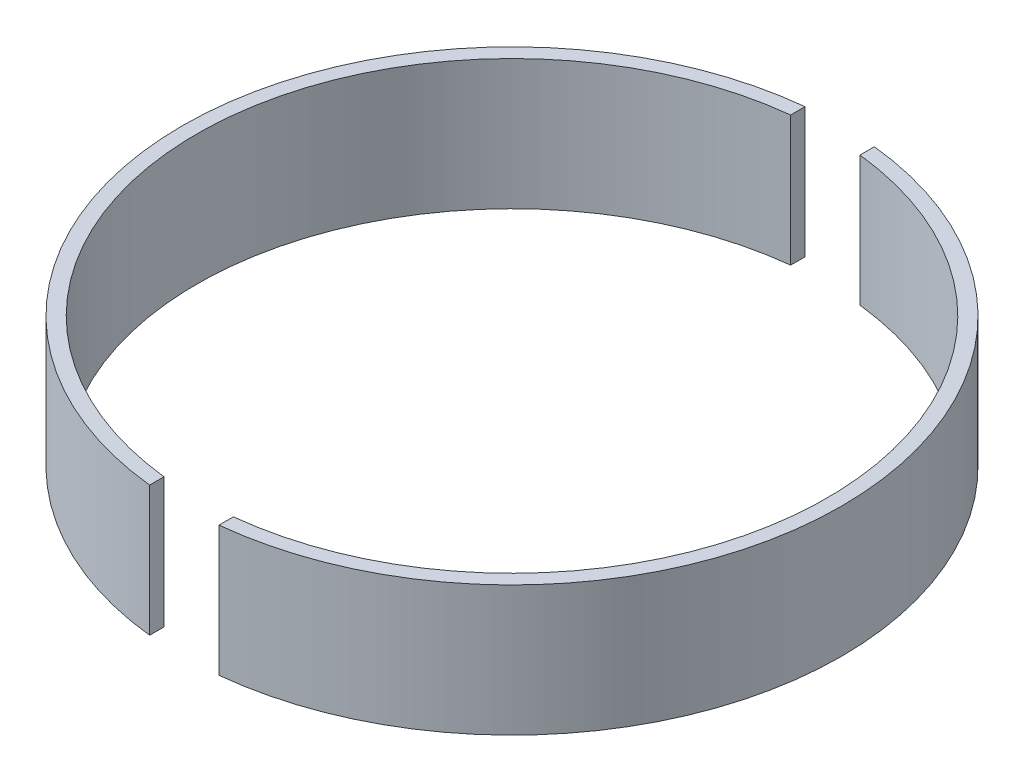
SolidWorks part; units mm, degrees
ref_plane "Plan de face" through (0, 0, 0) normal (0, 0, 1) x (1, 0, 0)
ref_plane "Plan de dessus" through (0, 0, 0) normal (0, 1, 0) x (1, 0, 0)
ref_plane "Plan de droite" through (0, 0, 0) normal (1, 0, 0) x (0, 0, -1)
sketch "Esquisse1" plane through (0, 0, 0) normal (0, 1, 0) x (1, 0, 0)
  circle A0 centre (0, 0) radius 76
  circle A1 centre (0, 0) radius 72.7
  dimension "D1" = 152
  dimension "D2" = 3.3
extrude "Boss.-Extru.1" add sketch "Esquisse1" along normal blind 30
ref_plane "Plan1" through (0, 15, 0) normal (0, -1, 0) x (-1, 0, 0)
sketch "Esquisse2" plane through (0, 0, 0) normal (0, -1, 0) x (1, 0, 0)
  line L0 (-8, -59.009) -> (-8, -72.009) construction
  line L1 (-8, 125.8717) -> (8, 125.8717)
  line L2 (-8, 125.8717) -> (-8, -81.6265)
  line L3 (-8, -81.6265) -> (8, -81.6265)
  line L4 (8, 125.8717) -> (8, -81.6265)
  line L5 (8, -72.009) -> (8, -59.009) construction
extrude "Enlèv. mat.-Extru.1" cut sketch "Esquisse2" against normal through all
